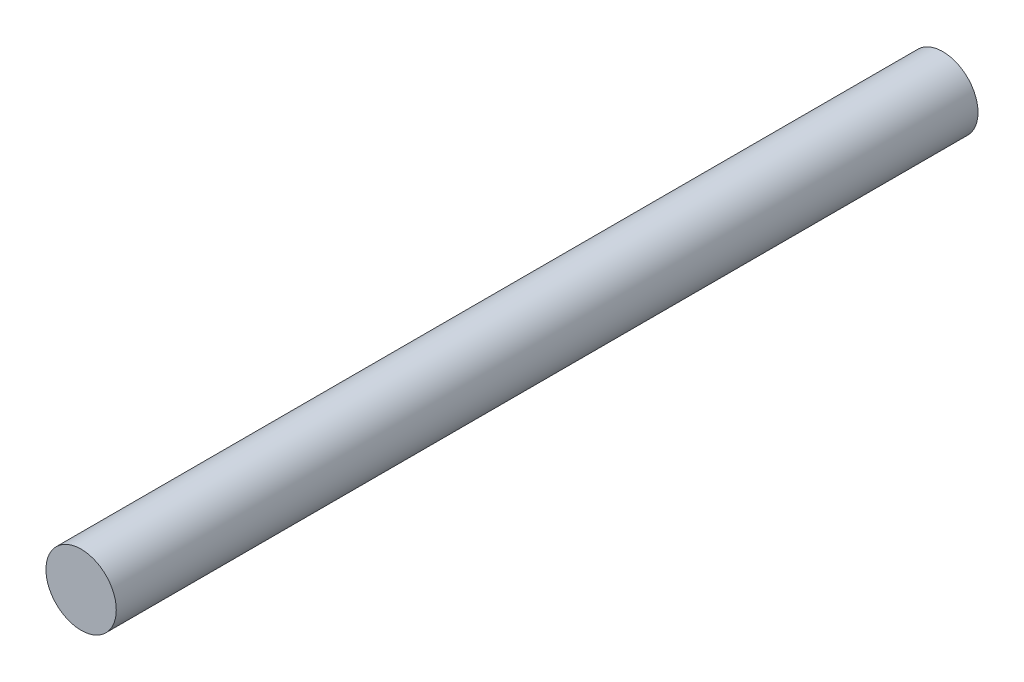
SolidWorks part; units mm, degrees
ref_plane "Front Plane" through (0, 0, 0) normal (0, 0, 1) x (1, 0, 0)
ref_plane "Top Plane" through (0, 0, 0) normal (0, 1, 0) x (1, 0, 0)
ref_plane "Right Plane" through (0, 0, 0) normal (1, 0, 0) x (0, 0, -1)
sketch "Shaft_Sketch" plane through (0, 0, 0) normal (0, 0, 1) x (1, 0, 0)
  circle A0 centre (0, 0) radius 4
  dimension "D1" = 8
extrude "Shaft" add sketch "Shaft_Sketch" along normal blind 98 from offset 49 separate body
